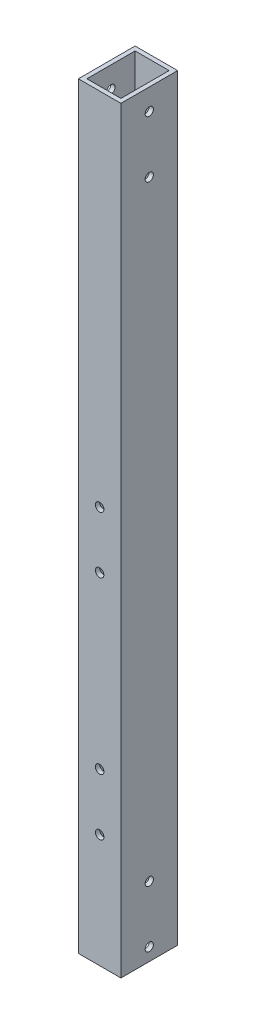
SolidWorks part; units mm, degrees
material "Thornel Mat VMA"
ref_plane "前视基准面" through (0, 0, 0) normal (0, 0, 1) x (1, 0, 0)
ref_plane "上视基准面" through (0, 0, 0) normal (0, 1, 0) x (1, 0, 0)
ref_plane "右视基准面" through (0, 0, 0) normal (1, 0, 0) x (0, 0, -1)
sketch "草图1" plane through (0, 0, 0) normal (0, 1, 0) x (1, 0, 0)
  line L1 (-7.5, -10) -> (7.5, -10)
  line L2 (-7.5, -10) -> (-7.5, 10)
  line L3 (-7.5, 10) -> (7.5, 10)
  line L4 (7.5, -10) -> (7.5, 10)
  line L5 (-7.5, -10) -> (7.5, 10) construction
  line L6 (-7.5, 10) -> (7.5, -10) construction
  point P0 (0, 0)
  dimension "D1" = 20
  dimension "D2" = 15
extrude "拉伸-薄壁1" add sketch "草图1" along normal blind 267 thin thin type one direction reverse wall 1.5
sketch "草图4" plane through (7.5, 0, 0) normal (1, 0, 0) x (0, 0, -1)
  line L0 (0, 0) -> (0, 267) construction
  line L1 (-10, 267) -> (10, 267) construction
  line L2 (-10, 0) -> (10, 0) construction
  circle A0 centre (0, 259.5) radius 1.45
  circle A1 centre (0, 239.5) radius 1.45
  circle A2 centre (0, 24.5) radius 1.45
  circle A3 centre (0, 4.5) radius 1.45
  dimension "D1" = 2.9
  dimension "D5" = 215
  dimension "D2" = 4.5
  dimension "D3" = 20
  dimension "D4" = 20
extrude "切除-拉伸2" cut sketch "草图4" against normal through all
sketch "草图5" plane through (0, 0, 10) normal (0, 0, 1) x (1, 0, 0)
  line L0 (0, 0) -> (0, 267) construction
  line L1 (-7.5, 267) -> (7.5, 267) construction
  line L2 (-7.5, 0) -> (7.5, 0) construction
  circle A0 centre (0, 40) radius 1.5
  circle A1 centre (0, 60) radius 1.5
  circle A2 centre (0, 120) radius 1.5
  circle A3 centre (0, 140) radius 1.5
  dimension "D1" = 3
  dimension "D2" = 20
  dimension "D3" = 20
  dimension "D4" = 60
  dimension "D5" = 40
extrude "切除-拉伸3" cut sketch "草图5" against normal through all
